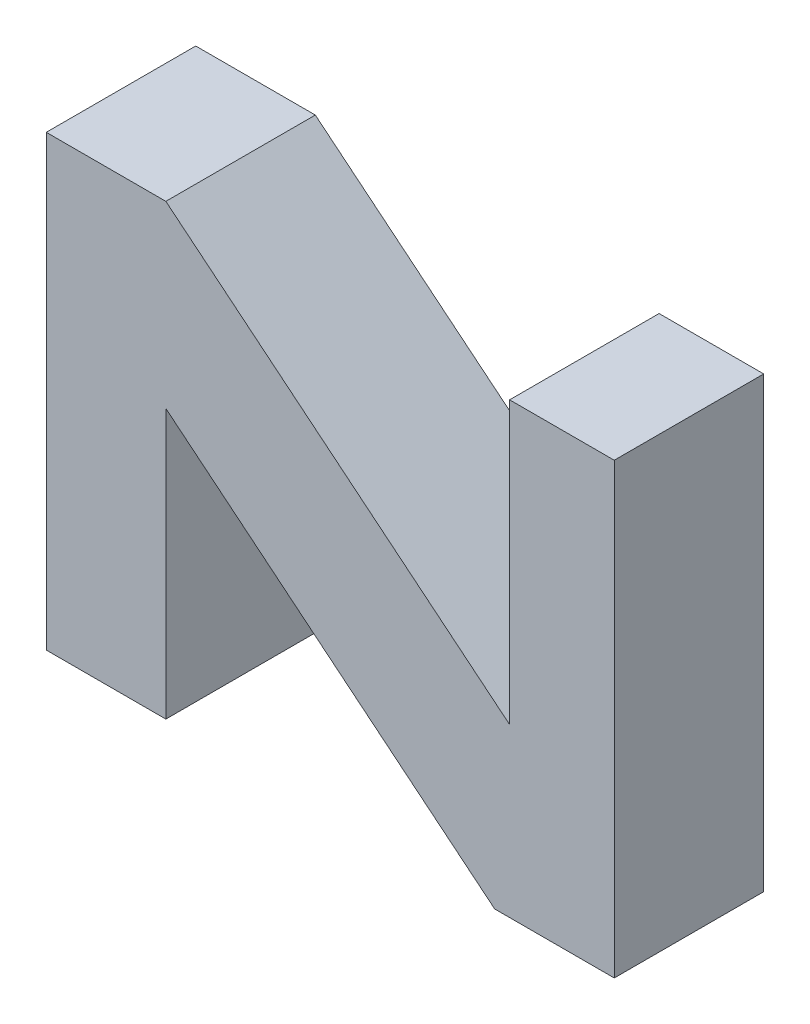
SolidWorks part; units mm, degrees
ref_plane "Front Plane" through (0, 0, 0) normal (0, 0, 1) x (1, 0, 0)
ref_plane "Top Plane" through (0, 0, 0) normal (0, 1, 0) x (1, 0, 0)
ref_plane "Right Plane" through (0, 0, 0) normal (1, 0, 0) x (0, 0, -1)
sketch "Sketch1" plane through (0, 0, 0) normal (0, 0, 1) x (1, 0, 0)
  line L0 (0, 0) -> (0, 30)
  line L1 (0, 30) -> (8, 30)
  line L2 (0, 0) -> (8, 0)
  line L3 (8, 0) -> (8, 18)
  line L4 (8, 30) -> (31, 11.1818)
  line L5 (8, 18) -> (30, 0)
  line L6 (30, 0) -> (38, 0)
  line L7 (31, 11.1818) -> (31, 30)
  line L8 (31, 30) -> (38, 30)
  line L9 (38, 30) -> (38, 0)
  dimension "D1" = 30
  dimension "D2" = 8
  dimension "D3" = 18
  dimension "D4" = 23
  dimension "D5" = 22
  dimension "D6" = 8
extrude "Boss-Extrude1" add sketch "Sketch1" along normal mid plane 10
